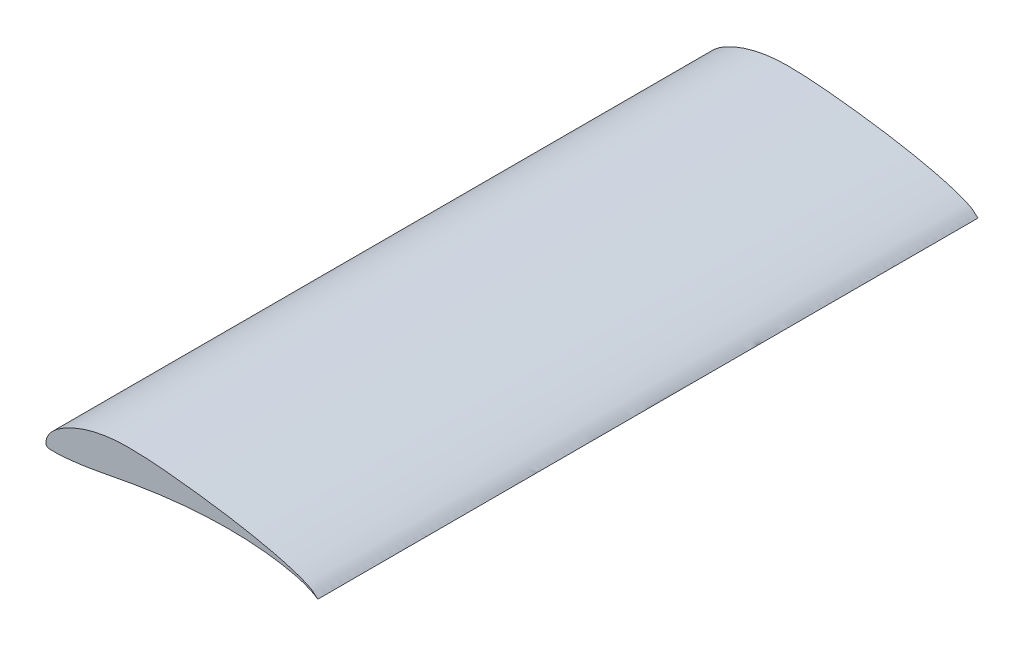
SolidWorks part; units mm, degrees
ref_plane "Front Plane" through (0, 0, 0) normal (0, 0, 1) x (1, 0, 0)
ref_plane "Top Plane" through (0, 0, 0) normal (0, 1, 0) x (1, 0, 0)
ref_plane "Right Plane" through (0, 0, 0) normal (1, 0, 0) x (0, 0, -1)
curve "Curve1"
  spline degree 3 poles (151.8102, 0.3958, 0) (152.5382, -0.0984, 0) (151.8999, 0.3772, 0) (151.4762, 0.7929, 0) (150.5354, 1.6612, 0) (149.4255, 2.5849, 0) (147.9072, 3.5162, 0) (146.0193, 4.4186, 0) (143.74, 5.3605, 0) (141.073, 6.3285, 0) (138.0307, 7.316, 0) (134.6288, 8.3144, 0) (130.8864, 9.3188, 0) (126.8242, 10.3203, 0) (122.4654, 11.3114, 0) (117.8361, 12.286, 0) (112.9645, 13.239, 0) (107.879, 14.1589, 0) (102.6118, 15.0441, 0) (97.1931, 15.8834, 0) (91.658, 16.6784, 0) (86.042, 17.4228, 0) (80.3858, 18.1141, 0) (74.7345, 18.7574, 0) (69.135, 19.3363, 0) (63.6328, 19.84, 0) (58.2667, 20.2402, 0) (53.0674, 20.5155, 0) (48.0637, 20.6344, 0) (43.2812, 20.6217, 0) (38.729, 20.3876, 0) (34.4052, 19.9131, 0) (30.2922, 19.2421, 0) (26.3891, 18.3728, 0) (22.6999, 17.3535, 0) (19.2401, 16.2022, 0) (16.0245, 14.9458, 0) (13.073, 13.591, 0) (10.3952, 12.1654, 0) (8.0055, 10.6852, 0) (5.9191, 9.1703, 0) (4.1367, 7.653, 0) (2.6842, 6.1167, 0) (1.5684, 4.5746, 0) (0.7443, 3.0743, 0) (0.2161, 1.6499, 0) (-0.0356, 0.3352, 0) (0.013, -0.7767, 0) (0.2993, -1.7966, 0) (1.3634, -2.3028, 0) (2.7941, -2.3738, 0) (4.7514, -2.4427, 0) (7.2127, -2.3365, 0) (10.1504, -2.1415, 0) (13.5317, -1.8291, 0) (17.322, -1.4063, 0) (21.5028, -0.8642, 0) (26.0721, -0.1065, 0) (31.0522, 0.8436, 0) (36.4679, 1.8776, 0) (42.2928, 2.9694, 0) (48.4902, 4.0736, 0) (55.0147, 5.1488, 0) (61.8156, 6.1591, 0) (68.8344, 7.0675, 0) (76.0079, 7.8474, 0) (83.2684, 8.4639, 0) (90.5429, 8.9009, 0) (97.7555, 9.1412, 0) (104.828, 9.1715, 0) (111.6814, 8.9899, 0) (118.2373, 8.6005, 0) (124.4169, 8.0085, 0) (130.1465, 7.2365, 0) (135.3515, 6.3069, 0) (139.971, 5.2509, 0) (143.9198, 4.1209, 0) (147.1515, 2.9148, 0) (149.4572, 1.8112, 0) (151.1572, 0.7907, 0) (151.8102, 0.3958, 0) (152.5382, -0.0984, 0) (151.8999, 0.3772, 0) knots -0.009748 -0.004147 -0.001 0 0.00098 0.003649 0.007483 0.012095 0.017526 0.024052 0.031783 0.040678 0.05071 0.061833 0.073989 0.087118 0.101145 0.115991 0.13157 0.147788 0.164551 0.181758 0.199312 0.217095 0.23499 0.252857 0.270541 0.287887 0.304773 0.321101 0.336806 0.3518 0.366031 0.379616 0.392653 0.40517 0.417172 0.428604 0.439419 0.449597 0.459102 0.467908 0.475988 0.483309 0.489875 0.495803 0.501149 0.505903 0.510047 0.513579 0.516447 0.51935 0.523823 0.529974 0.537716 0.546968 0.557637 0.56962 0.582804 0.597247 0.613135 0.630444 0.649056 0.668822 0.689595 0.71119 0.733427 0.756094 0.778989 0.80189 0.824567 0.846792 0.868338 0.888978 0.908492 0.926659 0.943286 0.958169 0.971136 0.981956 0.990252 0.995853 0.999 1 1.00098 1.003649 1.007483 periodic
sketch "Sketch1" plane through (0, 0, 0) normal (0, 0, 1) x (1, 0, 0)
  line L0 (0, 0) -> (177.8, 0) construction
  spline S2 degree 3 poles (177.112, 0.4618) (177.9612, -0.1148) (177.2167, 0.4401) (176.7224, 0.9252) (175.625, 1.9384) (174.3303, 3.0163) (172.5592, 4.103) (170.3568, 5.1562) (167.698, 6.2554) (164.5867, 7.3854) (161.0375, 8.538) (157.0689, 9.7034) (152.7031, 10.876) (147.9641, 12.0451) (142.8792, 13.2022) (137.4786, 14.3401) (131.7953, 15.453) (125.8626, 16.5271) (119.7178, 17.5609) (113.3963, 18.5411) (106.939, 19.4697) (100.3872, 20.3392) (93.7885, 21.1468) (87.1956, 21.8984) (80.6631, 22.5749) (74.2441, 23.1636) (67.9839, 23.6316) (61.9181, 23.9538) (56.0806, 24.0934) (50.5012, 24.0796) (45.1903, 23.8073) (40.1459, 23.2546) (35.3474, 22.4726) (30.7937, 21.4593) (26.4894, 20.2708) (22.4528, 18.9283) (18.7011, 17.4631) (15.2575, 15.8832) (12.1332, 14.2205) (9.3451, 12.494) (6.9106, 10.7272) (4.8309, 8.9574) (3.136, 7.1653) (1.834, 5.3664) (0.8722, 3.6164) (0.2558, 1.9547) (-0.0381, 0.4209) (0.0183, -0.8763) (0.3521, -2.0662) (1.5935, -2.657) (3.2626, -2.7401) (5.546, -2.8208) (8.4176, -2.6975) (11.8448, -2.4705) (15.7896, -2.1067) (20.2117, -1.6142) (25.0893, -0.9826) (30.4202, -0.0996) (36.2304, 1.0079) (42.5488, 2.2132) (49.3445, 3.4857) (56.575, 4.7728) (64.1869, 6.0259) (72.1214, 7.2032) (80.31, 8.2616) (88.6791, 9.1701) (97.1496, 9.8879) (105.6365, 10.3963) (114.0511, 10.6752) (122.3022, 10.7092) (130.2977, 10.496) (137.946, 10.0405) (145.1552, 9.3486) (151.8394, 8.4468) (157.9117, 7.3612) (163.3008, 6.1283) (167.9075, 4.8093) (171.6775, 3.4016) (174.3672, 2.1136) (176.3502, 0.9227) (177.112, 0.4618) (177.9612, -0.1148) (177.2167, 0.4401) knots -0.009748 -0.004147 -0.001 0 0.00098 0.003649 0.007483 0.012095 0.017526 0.024052 0.031783 0.040678 0.05071 0.061833 0.073989 0.087118 0.101145 0.115991 0.13157 0.147788 0.164551 0.181758 0.199312 0.217095 0.23499 0.252857 0.270541 0.287887 0.304773 0.321101 0.336806 0.3518 0.366031 0.379616 0.392653 0.40517 0.417172 0.428604 0.439419 0.449597 0.459102 0.467908 0.475988 0.483309 0.489875 0.495803 0.501149 0.505903 0.510047 0.513579 0.516447 0.51935 0.523823 0.529974 0.537716 0.546968 0.557637 0.56962 0.582804 0.597247 0.613135 0.630444 0.649056 0.668822 0.689595 0.71119 0.733427 0.756094 0.778989 0.80189 0.824567 0.846792 0.868338 0.888978 0.908492 0.926659 0.943286 0.958169 0.971136 0.981956 0.990252 0.995853 0.999 1 1.00098 1.003649 1.007483 only from (177.8, 0) to (177.8, 0)
  point P2 (0, 0)
  dimension "D1" = 177.8
extrude "Boss-Extrude1" add sketch "Sketch1" along normal blind 431.8
sketch "Sketch2" plane through (0, 0, 431.8) normal (0, 0, 1) x (1, 0, 0)
  line L0 (0, 0) -> (0, -14.4964) construction
  line L1 (0, 0) -> (152.4, 0) construction
  line L2 (152.4, 0) -> (152.4, -12.7) construction
  spline S0 degree 3 poles (151.8102, 0.3958) (152.5382, -0.0984) (151.8999, 0.3772) (151.4762, 0.7929) (150.5354, 1.6612) (149.4255, 2.5849) (147.9072, 3.5162) (146.0193, 4.4186) (143.74, 5.3605) (141.073, 6.3285) (138.0307, 7.316) (134.6288, 8.3144) (130.8864, 9.3188) (126.8242, 10.3203) (122.4654, 11.3114) (117.8361, 12.286) (112.9645, 13.239) (107.879, 14.1589) (102.6118, 15.0441) (97.1931, 15.8834) (91.658, 16.6784) (86.042, 17.4228) (80.3858, 18.1141) (74.7345, 18.7574) (69.135, 19.3363) (63.6328, 19.84) (58.2667, 20.2402) (53.0674, 20.5155) (48.0637, 20.6344) (43.2812, 20.6217) (38.729, 20.3876) (34.4052, 19.9131) (30.2922, 19.2421) (26.3891, 18.3728) (22.6999, 17.3535) (19.2401, 16.2022) (16.0245, 14.9458) (13.073, 13.591) (10.3952, 12.1654) (8.0055, 10.6852) (5.9191, 9.1703) (4.1367, 7.653) (2.6842, 6.1167) (1.5684, 4.5746) (0.7443, 3.0743) (0.2161, 1.6499) (-0.0356, 0.3352) (0.013, -0.7767) (0.2993, -1.7966) (1.3634, -2.3028) (2.7941, -2.3738) (4.7514, -2.4427) (7.2127, -2.3365) (10.1504, -2.1415) (13.5317, -1.8291) (17.322, -1.4063) (21.5028, -0.8642) (26.0721, -0.1065) (31.0522, 0.8436) (36.4679, 1.8776) (42.2928, 2.9694) (48.4902, 4.0736) (55.0147, 5.1488) (61.8156, 6.1591) (68.8344, 7.0675) (76.0079, 7.8474) (83.2684, 8.4639) (90.5429, 8.9009) (97.7555, 9.1412) (104.828, 9.1715) (111.6814, 8.9899) (118.2373, 8.6005) (124.4169, 8.0085) (130.1465, 7.2365) (135.3515, 6.3069) (139.971, 5.2509) (143.9198, 4.1209) (147.1515, 2.9148) (149.4572, 1.8112) (151.1572, 0.7907) (151.8102, 0.3958) (152.5382, -0.0984) (151.8999, 0.3772) knots -0.009748 -0.004147 -0.001 0 0.00098 0.003649 0.007483 0.012095 0.017526 0.024052 0.031783 0.040678 0.05071 0.061833 0.073989 0.087118 0.101145 0.115991 0.13157 0.147788 0.164551 0.181758 0.199312 0.217095 0.23499 0.252857 0.270541 0.287887 0.304773 0.321101 0.336806 0.3518 0.366031 0.379616 0.392653 0.40517 0.417172 0.428604 0.439419 0.449597 0.459102 0.467908 0.475988 0.483309 0.489875 0.495803 0.501149 0.505903 0.510047 0.513579 0.516447 0.51935 0.523823 0.529974 0.537716 0.546968 0.557637 0.56962 0.582804 0.597247 0.613135 0.630444 0.649056 0.668822 0.689595 0.71119 0.733427 0.756094 0.778989 0.80189 0.824567 0.846792 0.868338 0.888978 0.908492 0.926659 0.943286 0.958169 0.971136 0.981956 0.990252 0.995853 0.999 1 1.00098 1.003649 1.007483 only from (152.4, 0) to (152.4, 0) construction
sketch "Sketch3" plane through (0, 0, 0) normal (0, 0, -1) x (-1, 0, 0)
  line L0 (0, -14.4964) -> (0, 0) construction
  line L1 (0, 0) -> (-152.4, 0) construction
  line L2 (-152.4, 0) -> (-152.4, -12.7) construction
sketch "Sketch4" plane through (0, 0, 0) normal (0, 0, -1) x (-1, 0, 0)
  spline S1 degree 3 poles (-177.2167, 0.4401) (-177.9612, -0.1148) (-177.112, 0.4618) (-176.3502, 0.9227) (-174.3672, 2.1136) (-171.6775, 3.4016) (-167.9075, 4.8093) (-163.3008, 6.1283) (-157.9117, 7.3612) (-151.8394, 8.4468) (-145.1552, 9.3486) (-137.946, 10.0405) (-130.2977, 10.496) (-122.3022, 10.7092) (-114.0511, 10.6752) (-105.6365, 10.3963) (-97.1496, 9.8879) (-88.6791, 9.1701) (-80.31, 8.2616) (-72.1214, 7.2032) (-64.1869, 6.0259) (-56.575, 4.7728) (-49.3445, 3.4857) (-42.5488, 2.2132) (-36.2304, 1.0079) (-30.4202, -0.0996) (-25.0893, -0.9826) (-20.2117, -1.6142) (-15.7896, -2.1067) (-11.8448, -2.4705) (-8.4176, -2.6975) (-5.546, -2.8208) (-3.2626, -2.7401) (-1.5935, -2.657) (-0.3521, -2.0662) (-0.0183, -0.8763) (0.0381, 0.4209) (-0.2558, 1.9547) (-0.8722, 3.6164) (-1.834, 5.3664) (-3.136, 7.1653) (-4.8309, 8.9574) (-6.9106, 10.7272) (-9.3451, 12.494) (-12.1332, 14.2205) (-15.2575, 15.8832) (-18.7011, 17.4631) (-22.4528, 18.9283) (-26.4894, 20.2708) (-30.7937, 21.4593) (-35.3474, 22.4726) (-40.1459, 23.2546) (-45.1903, 23.8073) (-50.5012, 24.0796) (-56.0806, 24.0934) (-61.9181, 23.9538) (-67.9839, 23.6316) (-74.2441, 23.1636) (-80.6631, 22.5749) (-87.1956, 21.8984) (-93.7885, 21.1468) (-100.3872, 20.3392) (-106.939, 19.4697) (-113.3963, 18.5411) (-119.7178, 17.5609) (-125.8626, 16.5271) (-131.7953, 15.453) (-137.4786, 14.3401) (-142.8792, 13.2022) (-147.9641, 12.0451) (-152.7031, 10.876) (-157.0689, 9.7034) (-161.0375, 8.538) (-164.5867, 7.3854) (-167.698, 6.2554) (-170.3568, 5.1562) (-172.5592, 4.103) (-174.3303, 3.0163) (-175.625, 1.9384) (-176.7224, 0.9252) (-177.2167, 0.4401) (-177.9612, -0.1148) (-177.112, 0.4618) knots -0.007483 -0.003649 -0.00098 0 0.001 0.004147 0.009748 0.018044 0.028864 0.041831 0.056714 0.073341 0.091508 0.111022 0.131662 0.153208 0.175433 0.19811 0.221011 0.243906 0.266573 0.28881 0.310405 0.331178 0.350944 0.369556 0.386865 0.402753 0.417196 0.43038 0.442363 0.453032 0.462284 0.470026 0.476177 0.48065 0.483553 0.486421 0.489953 0.494097 0.498851 0.504197 0.510125 0.516691 0.524012 0.532092 0.540898 0.550403 0.560581 0.571396 0.582828 0.59483 0.607347 0.620384 0.633969 0.6482 0.663194 0.678899 0.695227 0.712113 0.729459 0.747143 0.76501 0.782905 0.800688 0.818242 0.835449 0.852212 0.86843 0.884009 0.898855 0.912882 0.926011 0.938167 0.94929 0.959322 0.968217 0.975948 0.982474 0.987905 0.992517 0.996351 0.99902 1 1.001 1.004147 1.009748 only from (-177.8, 0) to (-177.8, 0)
  spline S2 degree 3 poles (-177.2167, 0.4401) (-177.9612, -0.1148) (-177.112, 0.4618) (-176.3502, 0.9227) (-174.3672, 2.1136) (-171.6775, 3.4016) (-167.9075, 4.8093) (-163.3008, 6.1283) (-157.9117, 7.3612) (-151.8394, 8.4468) (-145.1552, 9.3486) (-137.946, 10.0405) (-130.2977, 10.496) (-122.3022, 10.7092) (-114.0511, 10.6752) (-105.6365, 10.3963) (-97.1496, 9.8879) (-88.6791, 9.1701) (-80.31, 8.2616) (-72.1214, 7.2032) (-64.1869, 6.0259) (-56.575, 4.7728) (-49.3445, 3.4857) (-42.5488, 2.2132) (-36.2304, 1.0079) (-30.4202, -0.0996) (-25.0893, -0.9826) (-20.2117, -1.6142) (-15.7896, -2.1067) (-11.8448, -2.4705) (-8.4176, -2.6975) (-5.546, -2.8208) (-3.2626, -2.7401) (-1.5935, -2.657) (-0.3521, -2.0662) (-0.0183, -0.8763) (0.0381, 0.4209) (-0.2558, 1.9547) (-0.8722, 3.6164) (-1.834, 5.3664) (-3.136, 7.1653) (-4.8309, 8.9574) (-6.9106, 10.7272) (-9.3451, 12.494) (-12.1332, 14.2205) (-15.2575, 15.8832) (-18.7011, 17.4631) (-22.4528, 18.9283) (-26.4894, 20.2708) (-30.7937, 21.4593) (-35.3474, 22.4726) (-40.1459, 23.2546) (-45.1903, 23.8073) (-50.5012, 24.0796) (-56.0806, 24.0934) (-61.9181, 23.9538) (-67.9839, 23.6316) (-74.2441, 23.1636) (-80.6631, 22.5749) (-87.1956, 21.8984) (-93.7885, 21.1468) (-100.3872, 20.3392) (-106.939, 19.4697) (-113.3963, 18.5411) (-119.7178, 17.5609) (-125.8626, 16.5271) (-131.7953, 15.453) (-137.4786, 14.3401) (-142.8792, 13.2022) (-147.9641, 12.0451) (-152.7031, 10.876) (-157.0689, 9.7034) (-161.0375, 8.538) (-164.5867, 7.3854) (-167.698, 6.2554) (-170.3568, 5.1562) (-172.5592, 4.103) (-174.3303, 3.0163) (-175.625, 1.9384) (-176.7224, 0.9252) (-177.2167, 0.4401) (-177.9612, -0.1148) (-177.112, 0.4618) knots -0.007483 -0.003649 -0.00098 0 0.001 0.004147 0.009748 0.018044 0.028864 0.041831 0.056714 0.073341 0.091508 0.111022 0.131662 0.153208 0.175433 0.19811 0.221011 0.243906 0.266573 0.28881 0.310405 0.331178 0.350944 0.369556 0.386865 0.402753 0.417196 0.43038 0.442363 0.453032 0.462284 0.470026 0.476177 0.48065 0.483553 0.486421 0.489953 0.494097 0.498851 0.504197 0.510125 0.516691 0.524012 0.532092 0.540898 0.550403 0.560581 0.571396 0.582828 0.59483 0.607347 0.620384 0.633969 0.6482 0.663194 0.678899 0.695227 0.712113 0.729459 0.747143 0.76501 0.782905 0.800688 0.818242 0.835449 0.852212 0.86843 0.884009 0.898855 0.912882 0.926011 0.938167 0.94929 0.959322 0.968217 0.975948 0.982474 0.987905 0.992517 0.996351 0.99902 1 1.001 1.004147 1.009748 only from (-177.8, 0) to (-177.8, 0)
  dimension "D1" = 0
sketch3d "3DSketch1"
  line L0 (0, 0, 431.8) -> (0, 0, 0) construction
